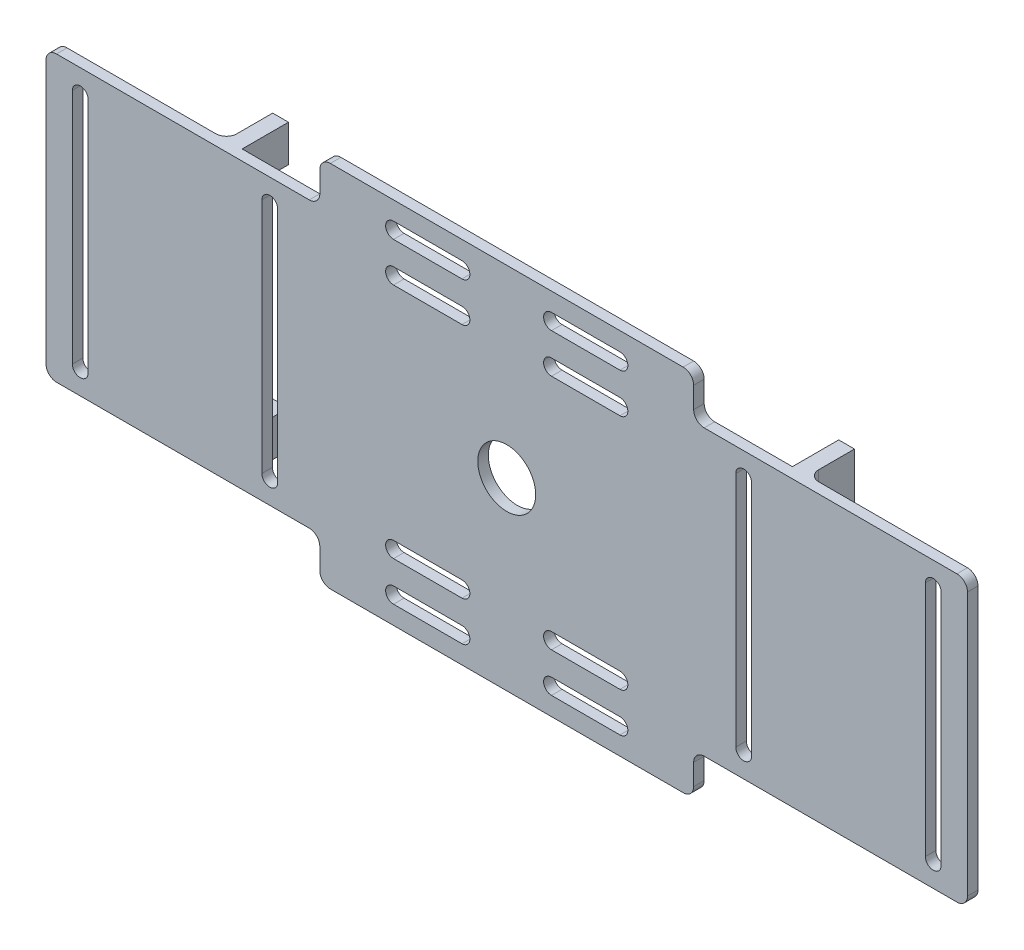
SolidWorks part; units mm, degrees
ref_plane "前基準面" through (0, 0, 0) normal (0, 0, 1) x (1, 0, 0)
ref_plane "上基準面" through (0, 0, 0) normal (0, 1, 0) x (1, 0, 0)
ref_plane "右基準面" through (0, 0, 0) normal (1, 0, 0) x (0, 0, -1)
sketch "草圖1" plane through (0, 0, 0) normal (0, 0, 1) x (1, 0, 0)
  line L0 (35.5, 33) -> (35.5, 29)
  line L1 (-33.5, 35) -> (33.5, 35)
  line L2 (-87.5, 25) -> (-87.5, -25)
  line L3 (-33.5, -35) -> (33.5, -35)
  line L4 (87.5, 25) -> (87.5, -25)
  line L5 (-85, 35) -> (85, -35) construction
  line L6 (-85, -35) -> (85, 35) construction
  line L7 (37.5, 27) -> (85.5, 27)
  line L8 (0, 72.342) -> (0, -45.5052) construction
  line L9 (-37.5, 27) -> (-85.5, 27)
  line L10 (124.9211, 0) -> (-91.026, 0) construction
  line L11 (-35.5, 33) -> (-35.5, 29)
  line L12 (37.5, -27) -> (85.5, -27)
  line L13 (35.5, -33) -> (35.5, -29)
  line L14 (-35.5, -33) -> (-35.5, -29)
  line L15 (-37.5, -27) -> (-85.5, -27)
  arc A0 (35.5, 33) -> (33.5, 35) centre (33.5, 33) ccw
  arc A1 (37.5, 27) -> (35.5, 29) centre (37.5, 29) cw
  arc A2 (87.5, 25) -> (85.5, 27) centre (85.5, 25) ccw
  arc A3 (-87.5, 25) -> (-85.5, 27) centre (-85.5, 25) cw
  arc A4 (-37.5, 27) -> (-35.5, 29) centre (-37.5, 29) ccw
  arc A5 (-35.5, 33) -> (-33.5, 35) centre (-33.5, 33) cw
  arc A6 (87.5, -25) -> (85.5, -27) centre (85.5, -25) cw
  arc A7 (37.5, -27) -> (35.5, -29) centre (37.5, -29) ccw
  arc A8 (35.5, -33) -> (33.5, -35) centre (33.5, -33) cw
  arc A9 (-35.5, -33) -> (-33.5, -35) centre (-33.5, -33) ccw
  arc A10 (-37.5, -27) -> (-35.5, -29) centre (-37.5, -29) cw
  arc A11 (-87.5, -25) -> (-85.5, -27) centre (-85.5, -25) ccw
  point P0 (0, 0)
  point P13 (35.5, 27)
  point P29 (-35.5, 27)
  point P39 (35.5, -27)
  point P49 (-35.5, -27)
  dimension "D1" = 2
  dimension "D2" = 2
  dimension "D3" = 2
  dimension "D4" = 175
  dimension "D5" = 70
  dimension "D6" = 52
  dimension "D7" = 8
extrude "填料-伸長1" add sketch "草圖1" along normal blind 2
sketch "草圖2" plane through (0, 0, 2) normal (0, 0, 1) x (1, 0, 0)
  line L0 (-1000, 0) -> (49000, 0) construction
  line L1 (45, -986.1952) -> (45, 49013.8048) construction
  line L2 (-81, -962.7943) -> (-81, 49037.2057) construction
  line L3 (45, -22.5) -> (45, 22.5) construction
  line L4 (43.5, -22.5) -> (43.5, 22.5)
  line L5 (46.5, -22.5) -> (46.5, 22.5)
  line L6 (-45, -1000) -> (-45, 49000) construction
  line L7 (-45, -22.5) -> (-45, 22.5) construction
  line L8 (-46.5, -22.5) -> (-46.5, 22.5)
  line L9 (-43.5, -22.5) -> (-43.5, 22.5)
  line L10 (0, -1000) -> (0, 49000) construction
  line L11 (-1005.6924, 30) -> (48994.3076, 30) construction
  line L12 (-1002.3566, -30) -> (48997.6434, -30) construction
  line L13 (21.5, 30) -> (8.5, 30) construction
  line L16 (21.5, 28.5) -> (8.5, 28.5)
  line L19 (81, -968.4295) -> (81, 49031.5705) construction
  line L20 (-81, -22.5) -> (-81, 22.5) construction
  line L21 (-82.5, -22.5) -> (-82.5, 22.5)
  line L22 (-79.5, -22.5) -> (-79.5, 22.5)
  line L23 (81, -22.5) -> (81, 22.5) construction
  line L24 (79.5, -22.5) -> (79.5, 22.5)
  line L25 (82.5, -22.5) -> (82.5, 22.5)
  line L26 (21.5, 31.5) -> (8.5, 31.5)
  line L27 (21.5, 22.5) -> (8.5, 22.5) construction
  line L28 (21.5, 21) -> (8.5, 21)
  line L29 (21.5, 24) -> (8.5, 24)
  line L30 (-21.5, 30) -> (-8.5, 30) construction
  line L31 (-21.5, 28.5) -> (-8.5, 28.5)
  line L32 (-21.5, 31.5) -> (-8.5, 31.5)
  line L33 (-21.5, 22.5) -> (-8.5, 22.5) construction
  line L34 (-21.5, 21) -> (-8.5, 21)
  line L35 (-21.5, 24) -> (-8.5, 24)
  line L36 (21.5, -30) -> (8.5, -30) construction
  line L37 (21.5, -28.5) -> (8.5, -28.5)
  line L38 (21.5, -31.5) -> (8.5, -31.5)
  line L39 (21.5, -22.5) -> (8.5, -22.5) construction
  line L40 (21.5, -21) -> (8.5, -21)
  line L41 (21.5, -24) -> (8.5, -24)
  line L42 (-21.5, -30) -> (-8.5, -30) construction
  line L43 (-21.5, -28.5) -> (-8.5, -28.5)
  line L44 (-21.5, -31.5) -> (-8.5, -31.5)
  line L45 (-21.5, -22.5) -> (-8.5, -22.5) construction
  line L46 (-21.5, -21) -> (-8.5, -21)
  line L47 (-21.5, -24) -> (-8.5, -24)
  arc A0 (43.5, -22.5) -> (46.5, -22.5) centre (45, -22.5) ccw
  arc A1 (46.5, 22.5) -> (43.5, 22.5) centre (45, 22.5) ccw
  arc A2 (-46.5, -22.5) -> (-43.5, -22.5) centre (-45, -22.5) ccw
  arc A3 (-43.5, 22.5) -> (-46.5, 22.5) centre (-45, 22.5) ccw
  arc A12 (-82.5, -22.5) -> (-79.5, -22.5) centre (-81, -22.5) ccw
  arc A13 (-79.5, 22.5) -> (-82.5, 22.5) centre (-81, 22.5) ccw
  arc A14 (79.5, -22.5) -> (82.5, -22.5) centre (81, -22.5) ccw
  arc A15 (82.5, 22.5) -> (79.5, 22.5) centre (81, 22.5) ccw
  circle A16 centre (0, 0) radius 5.5
  arc A17 (21.5, 28.5) -> (21.5, 31.5) centre (21.5, 30) ccw
  arc A18 (8.5, 31.5) -> (8.5, 28.5) centre (8.5, 30) ccw
  arc A19 (21.5, 21) -> (21.5, 24) centre (21.5, 22.5) ccw
  arc A20 (8.5, 24) -> (8.5, 21) centre (8.5, 22.5) ccw
  arc A21 (-21.5, 28.5) -> (-21.5, 31.5) centre (-21.5, 30) cw
  arc A22 (-8.5, 31.5) -> (-8.5, 28.5) centre (-8.5, 30) cw
  arc A23 (-21.5, 21) -> (-21.5, 24) centre (-21.5, 22.5) cw
  arc A24 (-8.5, 24) -> (-8.5, 21) centre (-8.5, 22.5) cw
  arc A25 (21.5, -28.5) -> (21.5, -31.5) centre (21.5, -30) cw
  arc A26 (8.5, -31.5) -> (8.5, -28.5) centre (8.5, -30) cw
  arc A27 (21.5, -21) -> (21.5, -24) centre (21.5, -22.5) cw
  arc A28 (8.5, -24) -> (8.5, -21) centre (8.5, -22.5) cw
  arc A29 (-21.5, -28.5) -> (-21.5, -31.5) centre (-21.5, -30) ccw
  arc A30 (-8.5, -31.5) -> (-8.5, -28.5) centre (-8.5, -30) ccw
  arc A31 (-21.5, -21) -> (-21.5, -24) centre (-21.5, -22.5) ccw
  arc A32 (-8.5, -24) -> (-8.5, -21) centre (-8.5, -22.5) ccw
  point P9 (45, 0)
  point P16 (-45, 0)
  point P31 (15, 30)
  point P39 (15, 22.5)
  point P47 (-81, 0)
  point P54 (81, 0)
  point P63 (-15, 30)
  point P70 (-15, 22.5)
  point P77 (15, -30)
  point P84 (15, -22.5)
  point P91 (-15, -30)
  point P98 (-15, -22.5)
  dimension "D10" = 1.5
  dimension "D20" = 11
  dimension "D12" = 8.5
  dimension "D2" = 45
  dimension "D3" = 3
  dimension "D4" = 90
  dimension "D5" = 45
  dimension "D6" = 3
  dimension "D7" = 45
  dimension "D8" = 60
  dimension "D9" = 30
  dimension "D11" = 13
  dimension "D13" = 2
  dimension "D14" = 162
  dimension "D15" = 81
  dimension "D16" = 3
  dimension "D17" = 45
  dimension "D18" = 45
  dimension "D19" = 3
extrude "除料-伸長1" cut sketch "草圖2" against normal through all
sketch "草圖5" plane through (0, 0, 2) normal (0, 0, 1) x (1, 0, 0)
  line L1 (-55.25, 27) -> (-52.25, 27)
  line L2 (-55.25, 27) -> (-55.25, -27)
  line L3 (-55.25, -27) -> (-52.25, -27)
  line L4 (-52.25, 27) -> (-52.25, -27)
  line L6 (0, 48.2539) -> (0, -45.9001) construction
  line L7 (52.25, 27) -> (52.25, -27)
  line L8 (55.25, -27) -> (52.25, -27)
  line L9 (55.25, 27) -> (55.25, -27)
  line L10 (55.25, 27) -> (52.25, 27)
  line L11 (-37.5, 27) -> (-85.5, 27) construction
  line L13 (-85.5, -27) -> (-37.5, -27) construction
  dimension "D1" = 3
  dimension "D2" = 52.25
extrude "填料-伸長2" add sketch "草圖5" against normal blind 10.8 contours L2 L3 L4 L1 | L7 L8 L9 L10
fillet "圓角1" radius 2 1 edges at (55.25, 0, 0)
sketch "草圖6" plane through (0, 0, -8.8) normal (0, 0, -1) x (-1, 0, 0)
  line L0 (-19.1896, 0) -> (94.9262, 0) construction
  line L1 (55.25, 27) -> (55.25, -27) construction
  line L2 (52.25, -20) -> (55.25, -20)
  line L3 (52.25, -20) -> (52.25, 20)
  line L4 (52.25, 20) -> (55.25, 20)
  line L5 (55.25, -20) -> (55.25, 20)
  line L6 (52.25, -20) -> (55.25, 20) construction
  line L7 (52.25, 20) -> (55.25, -20) construction
  line L8 (52.25, 27) -> (52.25, -27) construction
  point P2 (53.75, 0)
  dimension "D1" = 40
extrude "除料-伸長3" cut sketch "草圖6" against normal blind 6
fillet "圓角2" radius 2 2 edges at (-53.75, -20, -2.8) (-53.75, 20, -2.8)
fillet "圓角3" radius 2 1 edges at (-55.25, 0, 0)
